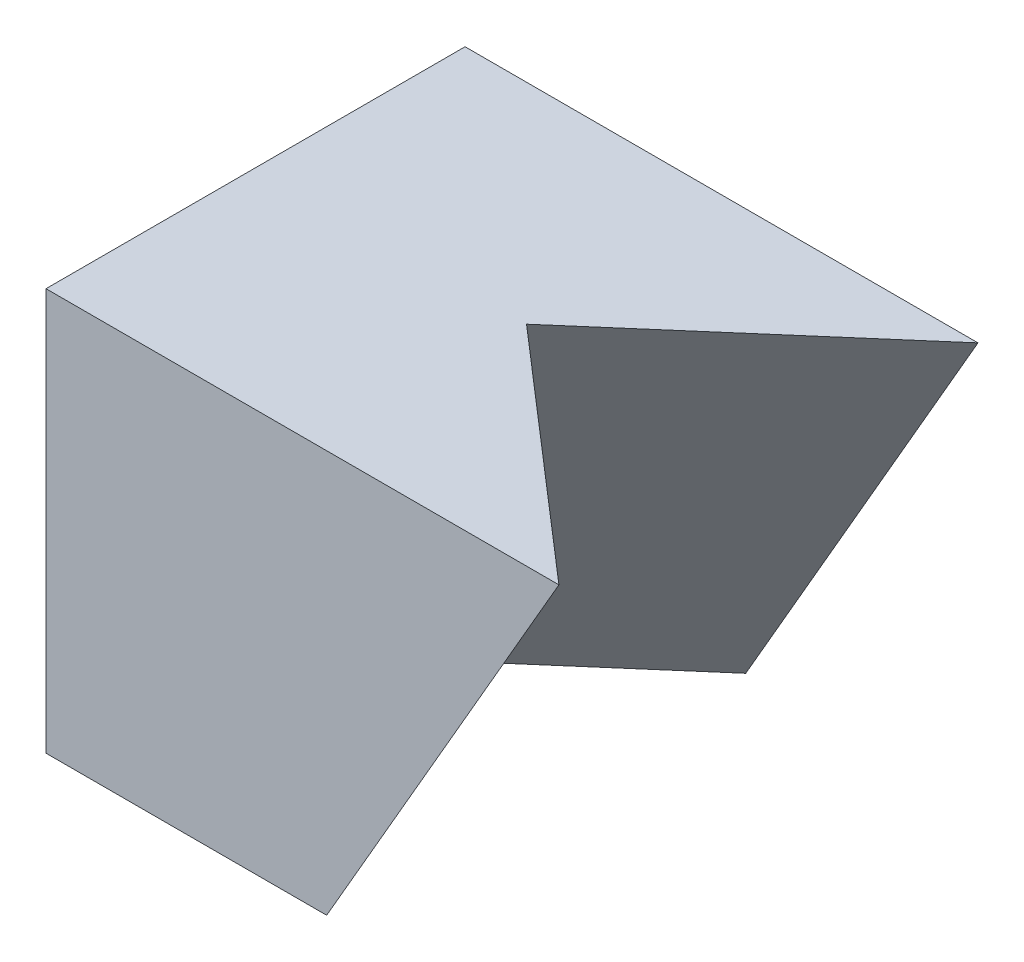
SolidWorks part; units mm, degrees
ref_plane "Front Plane" through (0, 0, 0) normal (0, 0, 1) x (1, 0, 0)
ref_plane "Top Plane" through (0, 0, 0) normal (0, 1, 0) x (1, 0, 0)
ref_plane "Right Plane" through (0, 0, 0) normal (1, 0, 0) x (0, 0, -1)
sketch "Sketch1" plane through (0, 0, 0) normal (0, 1, 0) x (1, 0, 0)
  line L1 (-17.5, -12.5) -> (17.5, -12.5)
  line L2 (-17.5, -12.5) -> (-17.5, 12.5)
  line L3 (-17.5, 12.5) -> (17.5, 12.5)
  line L4 (17.5, -12.5) -> (17.5, 12.5)
  line L5 (-17.5, -12.5) -> (17.5, 12.5) construction
  line L6 (-17.5, 12.5) -> (17.5, -12.5) construction
  point P0 (0, 0)
  dimension "D1" = 35
  dimension "D2" = 25
extrude "Boss-Extrude1" add sketch "Sketch1" along normal blind 24
sketch "Sketch3" plane through (0, 0, -12.5) normal (0, 0, -1) x (-1, 0, 0)
  line L0 (-17.5, 0) -> (17.5, 0) construction
  line L1 (-17.5, 0) -> (17.5, 0)
  line L2 (17.5, 0) -> (-13.2232, -17.738)
  dimension "D1" = 30
ref_plane "Plane1" through (-4.375, -7.5777, 0) normal (-0.5, -0.866, 0) x (-0.866, 0.5, 0)
sketch "Sketch4" plane through (-4.375, -7.5777, 0) normal (-0.5, -0.866, 0) x (-0.866, 0.5, 0)
  line L0 (-7.25, 20.4054) -> (13.1554, 0)
  line L1 (-7.25, 20.4054) -> (-27.6554, 0)
  line L2 (13.1554, 0) -> (-7.25, -20.4054)
  line L3 (-27.6554, 0) -> (-7.25, -20.4054)
  line L4 (-7.25, 20.4054) -> (-7.25, -20.4054) construction
  line L5 (13.1554, 0) -> (-27.6554, 0) construction
  line L6 (13.1554, 0) -> (15.1554, 0) construction
  line L8 (15.1554, 12.5) -> (15.1554, -12.5) construction
  line L9 (15.1554, 12.5) -> (15.1554, -12.5) construction
  point P0 (-31.4697, 0)
  point P1 (-7.25, 0)
  point P3 (-15.1554, 12.5)
  dimension "D1" = 2
extrude "Cut-Extrude1" cut sketch "Sketch4" against normal through all
sketch "Sketch5" plane through (-17.5, 0, 0) normal (-1, 0, 0) x (0, 0, 1)
  line L0 (-12.5, 24) -> (12.5, 24) construction
  line L2 (-10.5, 22) -> (10.5, 22) construction
  line L3 (-10.5, 22) -> (-10.5, 9.5) construction
  line L4 (-10.5, 9.5) -> (10.5, 9.5) construction
  line L5 (10.5, 22) -> (10.5, 9.5) construction
  line L6 (12.5, 24) -> (12.5, 0) construction
  circle A0 centre (-10.5, 22) radius 0.95
  circle A1 centre (10.5, 22) radius 0.95
  circle A2 centre (10.5, 9.5) radius 0.95
  circle A3 centre (-10.5, 9.5) radius 0.95
  dimension "D1" = 1.9
  dimension "D2" = 2
  dimension "D3" = 2
  dimension "D4" = 21
  dimension "D5" = 12.5
extrude "Cut-Extrude2" cut sketch "Sketch5" against normal blind 7
